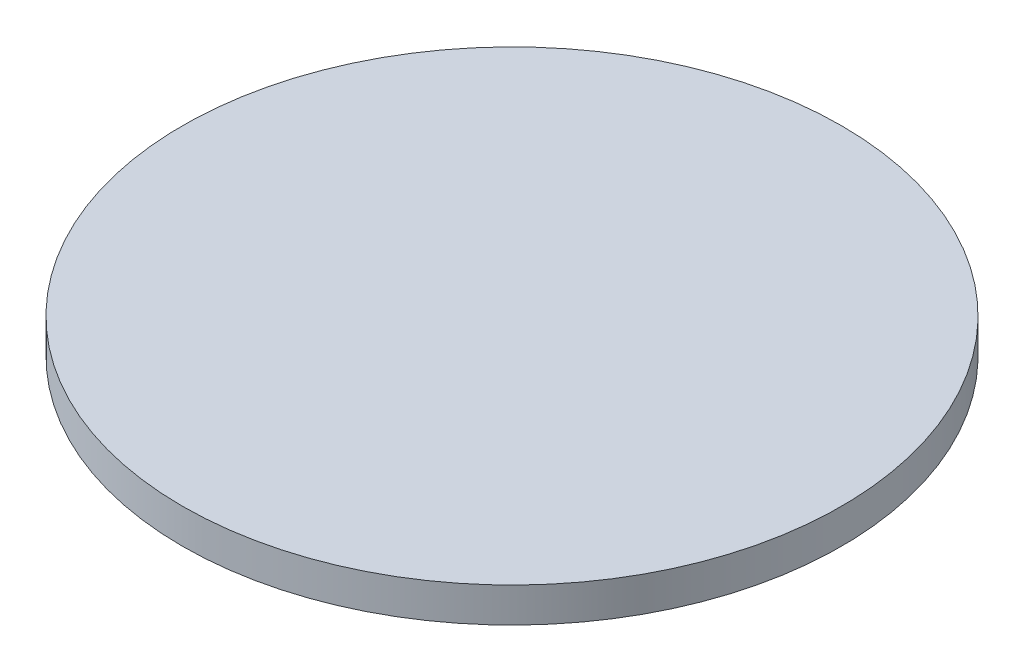
SolidWorks part; units mm, degrees
ref_plane "Front Plane" through (0, 0, 0) normal (0, 0, 1) x (1, 0, 0)
ref_plane "Top Plane" through (0, 0, 0) normal (0, 1, 0) x (1, 0, 0)
ref_plane "Right Plane" through (0, 0, 0) normal (1, 0, 0) x (0, 0, -1)
sketch "Sketch1" plane through (0, 0, 0) normal (0, 1, 0) x (1, 0, 0)
  circle A0 centre (0, 0) radius 120.65
extrude "Boss-Extrude1" add sketch "Sketch1" along normal blind 12.7
